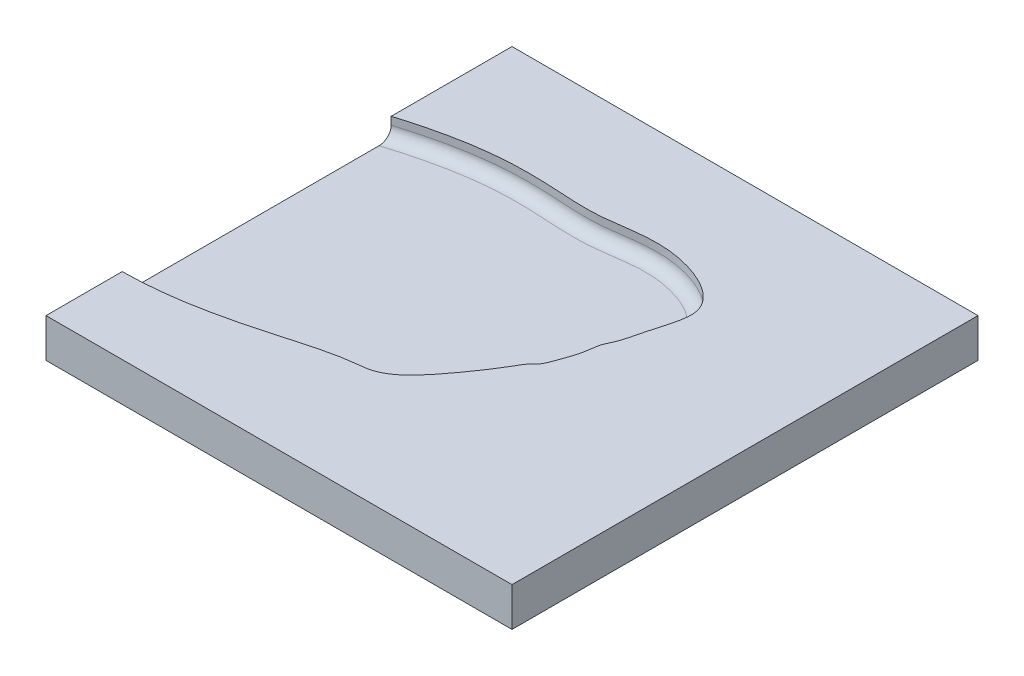
SolidWorks part; units mm, degrees
ref_plane "Piano frontale" through (0, 0, 0) normal (0, 0, 1) x (1, 0, 0)
ref_plane "Piano superiore" through (0, 0, 0) normal (0, 1, 0) x (1, 0, 0)
ref_plane "Piano destro" through (0, 0, 0) normal (1, 0, 0) x (0, 0, -1)
sketch "Schizzo2" plane through (0, 0, 0) normal (0, 1, 0) x (1, 0, 0)
  line L0 (-2.6639, -29.6899) -> (117.3361, -29.6899)
  line L1 (117.3361, -29.6899) -> (117.3361, -149.6899)
  line L2 (117.3361, -149.6899) -> (-2.6639, -149.6899)
  line L3 (-2.6639, -149.6899) -> (-2.6639, -29.6899)
  dimension "D1" = 120
  dimension "D2" = 120
extrude "Estrusione-Estrusione2" add sketch "Schizzo2" along normal blind 10
sketch "Schizzo4" plane through (0, 0, 0) normal (0, -1, 0) x (1, 0, 0)
  line L0 (57.3361, 149.6899) -> (57.3361, 29.6899) construction
  line L1 (-2.6639, 149.6899) -> (117.3361, 149.6899) construction
  line L2 (117.3361, 29.6899) -> (-2.6639, 29.6899) construction
  line L4 (117.3361, 149.6899) -> (117.3361, 29.6899) construction
  line L5 (117.3361, 89.6899) -> (-2.6639, 89.6899) construction
  line L6 (-2.6639, 29.6899) -> (-2.6639, 149.6899) construction
  point P6 (57.3361, 109.6899)
  point P13 (57.3361, 69.6899)
  dimension "D1" = 20
  dimension "D2" = 20
hole_wizard "Foro per Vite M2.5-2" positions "Schizzo3D5" profile "Schizzo9" hole size "M2.5" standard "IS"
sketch3d "Schizzo3D5"
  point P0 (57.3361, 0, 69.6899)
  point P3 (57.3361, 0, 109.6899)
sketch "Schizzo9" plane through (57.3361, 0, 69.6899) normal (1, 0, 0) x (0, 0, -1)
  line L0 (0, 0) -> (0, 4.9313)
  line L1 (0, 4.9313) -> (1.55, 4)
  line L2 (1.55, 4) -> (1.55, 0)
  line L5 (1.55, 0) -> (0, 0)
  line L10 (0, 4.9313) -> (-1.55, 4) construction
  line L11 (0, -6.35) -> (0, 107.95) construction
  dimension "Hole Dia." = 3.1
  dimension "Hole Depth" = 4
  dimension "Drill Angle" = 118
sketch "Schizzo10" plane through (0, 10, 0) normal (0, 1, 0) x (1, 0, 0)
  line L0 (325.8013, 481.888) -> (1458.369, 561.0848) construction
  line L1 (57.3361, -29.6899) -> (-2.6639, -29.6899) construction
  line L2 (-2.6639, -29.6899) -> (-2.6639, -37.2776) construction
  line L5 (-2.6639, -110.4364) -> (-2.6639, -149.6899) construction
  line L6 (-9.3592, -53.2049) -> (57.3361, -53.2049) construction
  line L7 (57.3361, -53.2049) -> (57.3361, -126.1749) construction
  line L8 (-2.6639, -60.8026) -> (-2.6639, -130.0631)
  line L12 (-2.6639, -29.6899) -> (-2.6639, -149.6899) construction
  line L14 (-2.6639, -29.6899) -> (80.3361, -29.6899) construction
  line L15 (117.3361, -29.6899) -> (-2.6639, -29.6899) construction
  line L16 (80.3361, -29.6899) -> (80.3361, -161.99) construction
  spline S0 degree 3 poles (-2.6639, -60.8026) (24.1205, -52.57) (39.1866, -58.9894) (63.0383, -52.7259) (83.8084, -61.2534) (78.3529, -73.9415) (76.9698, -81.4254) (75.0667, -84.9588) (74.8672, -88.8365) (73.3371, -92.8296) (72.181, -96.6491) (69.3445, -99.0467) (69.3355, -100.716) (55.0642, -120.5593) (41.363, -119.4122) (18.7745, -129.9201) (-2.6639, -130.0631) knots 0 0 0 0 0.230828 0.329752 0.44805 0.523336 0.556692 0.562732 0.583727 0.608943 0.641848 0.652122 0.711678 0.742833 0.807026 1 1 1 1
  point P17 (57.3361, -99.3307)
  point P27 (57.3361, -97.2197)
  point P29 (71.2482, -97.4116)
  dimension "D1" = 60
  dimension "D2" = 66.6954
  dimension "D3" = 72.97
  dimension "D4" = 83
extrude "Taglio-Estrusione1" cut sketch "Schizzo10" against normal blind 5
fillet "Raccordo1" radius 3 1 edges
